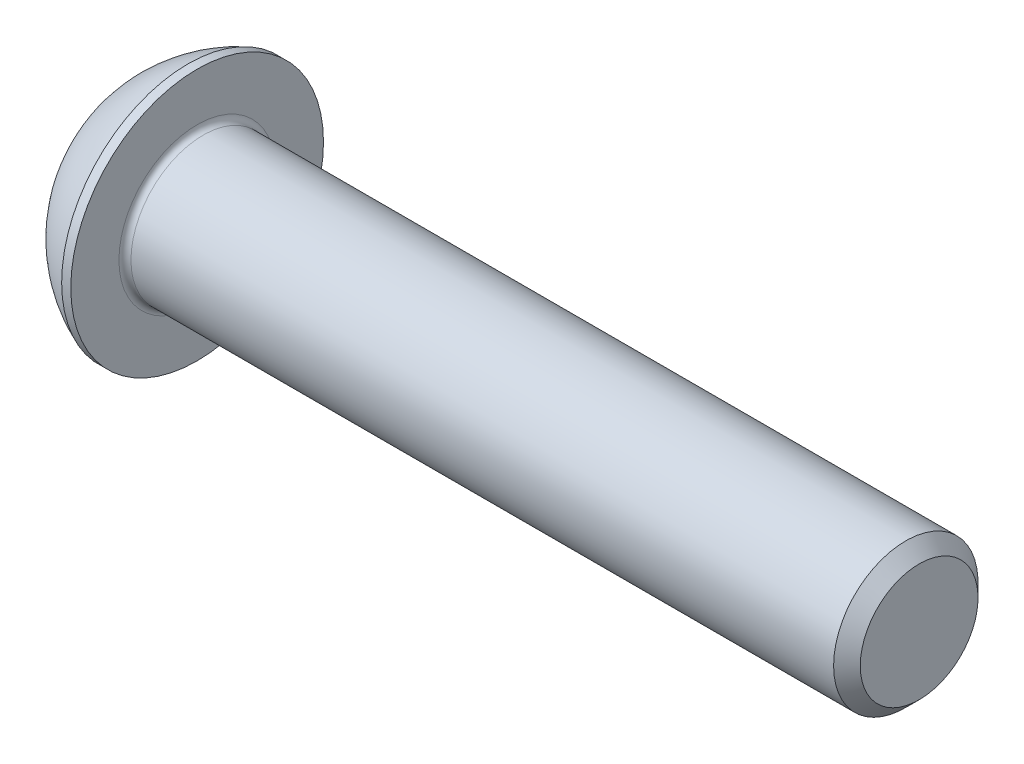
SolidWorks part; units mm, degrees
ref_plane "Plane1" through (0, 0, 0) normal (0, 0, 1) x (1, 0, 0)
ref_plane "Plane2" through (0, 0, 0) normal (0, 1, 0) x (1, 0, 0)
ref_plane "Plane3" through (0, 0, 0) normal (1, 0, 0) x (0, 0, -1)
sketch "BodySke" plane through (0, 0, 0) normal (0, 0, 1) x (1, 0, 0)
  line L0 (33.3, 0) -> (33.3, 2.4455)
  line L1 (32.7455, 3) -> (3.3, 3)
  line L2 (3.3, 3) -> (3.3, 5.25)
  line L3 (3.3, 5.25) -> (2.92, 5.25)
  line L4 (0, 0) -> (101.6, 0) construction
  line L5 (3.3, -5.25) -> (2.92, -5.25) construction
  line L6 (55.6768, -3) -> (3.3, -3) construction
  line L7 (33.3, 0) -> (0, 0)
  line L8 (0, 2.625) -> (0, -2.625) construction
  line L9 (0, 0) -> (0, 2.625)
  line L10 (33.3, 2.4455) -> (32.7455, 3)
  line L11 (33.3, -2.4455) -> (32.7455, -3) construction
  line L12 (4.3, 9.525) -> (4.3, -3) construction
  line L13 (3.3, 9.525) -> (3.3, -3) construction
  arc A1 (0, 2.625) -> (2.92, 5.25) centre (4.9997, 0) cw
  dimension "Diameter" = 6
  dimension "Length" = 30
  dimension "Head_dia" = 10.5
  dimension "D1" = 5.25
  dimension "Head_ht" = 3.3
  dimension "Head_side_ht" = 0.38
  dimension "Minor_dia" = 4.891
  dimension "Body_ch_ang" = 45
  dimension "Advance" = 1
  dimension "Thread_nom" = 30
revolve "BaseBody" add sketch "BodySke" angle 360 about L4
cosmetic thread "ThreadCosmetic" parameters "Thread_length"=28, "Thread_minor"=4.891
fillet "Fillet1" radius 0.25 1 edges at (3.3, 0, 3)
sketch "Sketch2" plane through (0, 0, 0) normal (0, 0, 1) x (1, 0, 0)
  line L0 (0, 2) -> (2.08, 2)
  line L1 (2.08, 2) -> (3.2347, 0)
  line L3 (3.2347, 0) -> (0, 0)
  line L4 (0, 0) -> (0, 2)
  line L5 (0, -2) -> (2.08, -2) construction
  line L6 (0, 0) -> (47.625, 0) construction
  dimension "D2" = 60
  dimension "PreBroach_depth" = 2.08
  dimension "PreBroach_dia" = 4
revolve "PreBroach" cut sketch "Sketch2" angle 360 about L6
sketch "Sketch3" plane through (0, 0, 0) normal (1, 0, 0) x (0, 0, -1)
  line L0 (-2, -1.1547) -> (-2, 1.1547)
  line L1 (-2, 1.1547) -> (0, 2.3094)
  line L2 (0, 2.3094) -> (2, 1.1547)
  line L3 (2, 1.1547) -> (2, -1.1547)
  line L4 (2, -1.1547) -> (0, -2.3094)
  line L5 (0, -2.3094) -> (-2, -1.1547)
  dimension "Hex_size" = 4
  dimension "D3" = 4
  dimension "D1" = 2
  dimension "D2" = 2
extrude "Hex" cut sketch "Sketch3" along normal blind 2.08
sketch "ThdSchSke" plane through (0, 0, 0) normal (0, 0, 1) x (1, 0, 0)
  line L0 (5.3, -2.4455) -> (4.9117, -3)
  line L1 (5.3, -2.4455) -> (5.6883, -3)
  line L2 (5.6883, -3) -> (5.6883, -3.75)
  line L3 (-3.175, 0) -> (5.1513, 0) construction
  line L5 (5.6883, -3.75) -> (4.9117, -3.75)
  line L6 (4.9117, -3.75) -> (4.9117, -3)
  dimension "Diameter" = 6
  dimension "Thread_minor" = 4.891
  dimension "SideAngle" = 55
  dimension "VeeAngle" = 70
  dimension "Overcut" = 7.5
  dimension "Start" = 5.3
revolve "ThreadSchematic" [suppressed] cut sketch "ThdSchSke" angle 360 about L3
pattern_linear "ThdSchPat" [suppressed]
equation "\"D1@BodySke\" = \"Head_dia@BodySke\" * .5"
equation "\"Thread_minor@ThreadCosmetic\" = \"Minor_dia@BodySke\""
equation "\"D1@Sketch3\" = \"Hex_size@Sketch3\" / 2"
equation "\"D2@Sketch3\" = \"D1@Sketch3\""
equation "\"D3@Sketch3\" = \"Hex_size@Sketch3\""
equation "\"Thread_length@ThreadCosmetic\" = ((sgn( (\"Length@BodySke\" - \"Advance@BodySke\" * 2.0) - \"Thread_nom@BodySke\" )-1)*( (\"Length@BodySke\" - \"Advance@BodySke\" * 2.0) - \"Thread_nom@BodySke\" ))/-2+ \"Thread_nom@BodySke\""
equation "\"Thread_minor@ThdSchSke\" = \"Minor_dia@BodySke\""
equation "\"Diameter@ThdSchSke\" = \"Diameter@BodySke\""
equation "\"Overcut@ThdSchSke\" = \"Diameter@BodySke\" * 1.25"
equation "\"Start@ThdSchSke\" = \"Head_ht@BodySke\" + \"Length@BodySke\" - \"Thread_length@ThreadCosmetic\"  '---Non-countersunk---"
equation "\"Num_threads@ThdSchPat\" = int( \"Thread_length@ThreadCosmetic\" / \"Advance@BodySke\" + 0.999 )  + 1"
equation "\"Advance@ThdSchPat\" = \"Thread_length@ThreadCosmetic\" /  (\"Num_threads@ThdSchPat\" - 1) 'relax it"
equation "\"Num_threads@ThdSchPat\" = \"Num_threads@ThdSchPat\" - sgn( \"Num_threads@ThdSchPat\" - 1) '---chamfered tips only---"
